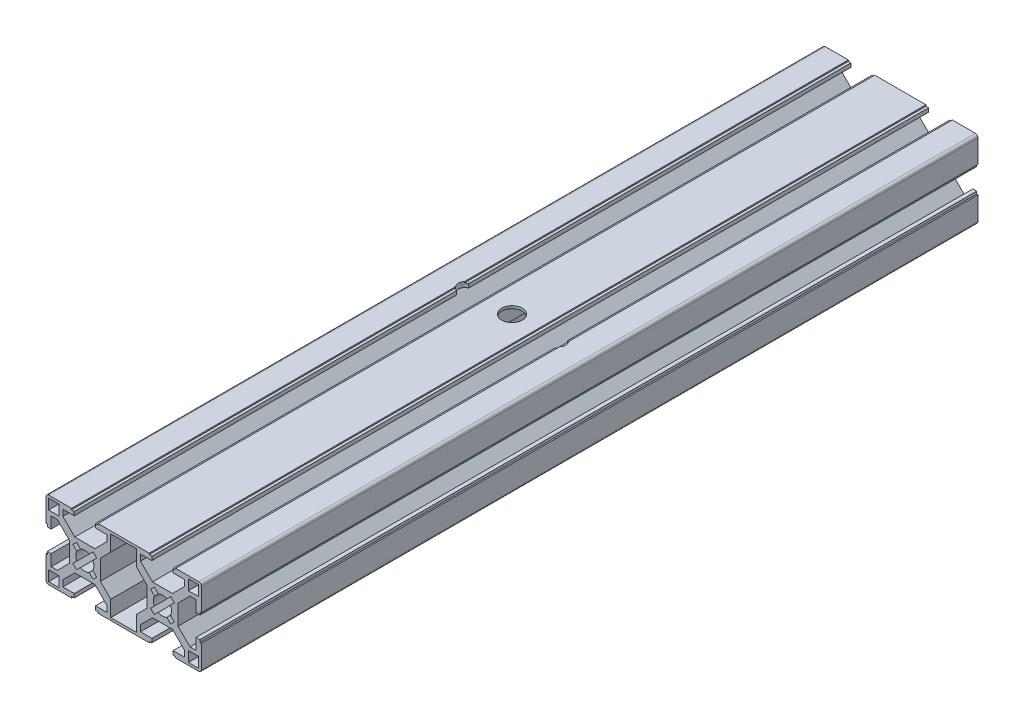
SolidWorks part; units mm, degrees
material "6063-O"
ref_plane "Plano frontal" through (0, 0, 0) normal (0, 0, 1) x (1, 0, 0)
ref_plane "Plano superior" through (0, 0, 0) normal (0, 1, 0) x (1, 0, 0)
ref_plane "Plano direito" through (0, 0, 0) normal (1, 0, 0) x (0, 0, -1)
sketch "Esboço1" plane through (0, 0, 0) normal (0, 0, 1) x (1, 0, 0)
  line L5 (0, 0) -> (-17.7944, 17.7944) construction
  line L6 (0, 3.5) -> (0, 6)
  line L8 (0, 6) -> (-3.8787, 6)
  line L9 (-3.5, 0) -> (-6, 0)
  line L48 (-6, 0) -> (-6, 3.8787)
  line L49 (-3.8787, 6) -> (-8.5, 10.6213)
  line L50 (-6, 3.8787) -> (-10.6213, 8.5)
  line L51 (0, 0) -> (-12.921, 0) construction
  line L52 (-8.5, 13) -> (-4.1, 13)
  line L53 (-4.1, 13) -> (-4.1, 14.5)
  line L54 (-4.1, 14.5) -> (-5.1, 14.5)
  line L55 (-5.1, 14.5) -> (-5.1, 15)
  line L56 (-5.1, 15) -> (-15, 15)
  line L57 (-15, 5.1) -> (-15, 15)
  line L58 (-14.5, 5.1) -> (-15, 5.1)
  line L59 (-14.5, 4.1) -> (-14.5, 5.1)
  line L60 (-13, 4.1) -> (-14.5, 4.1)
  line L61 (-13, 8.5) -> (-13, 4.1)
  line L62 (-1.6646, 3.0788) -> (-3.182, 4.5962)
  line L63 (-3.0788, 1.6646) -> (-4.5962, 3.182)
  line L64 (-4.5962, 3.182) -> (-3.182, 4.5962)
  line L65 (-8.5, 13) -> (-8.5, 10.6213)
  line L66 (-10, 14) -> (-14, 14)
  line L67 (-10, 14) -> (-10, 10)
  line L68 (-10, 10) -> (-14, 10)
  line L69 (-14, 14) -> (-14, 10)
  line L70 (-10, 14) -> (-14, 10) construction
  line L71 (-10, 10) -> (-14, 14) construction
  line L72 (-13, 8.5) -> (-10.6213, 8.5)
  circle A1 centre (0, 0) radius 3.5
  point P25 (-12, 12)
  dimension "D5" = 10.9
  dimension "D9" = 5.5
  dimension "D10" = 2
  dimension "D11" = 4
  dimension "D12" = 4
  dimension "D13" = 1
  dimension "D1" = 7
  dimension "D2" = 6
  dimension "D3" = 3
  dimension "D4" = 9.9
  dimension "D6" = 0.5
  dimension "D7" = 1.5
  dimension "D8" = 15
  dimension "D14" = 6.5
extrude "Ressalto-extrusão1" add sketch "Esboço1" along normal blind 300 contours A1 L6 L8 L49 L65 L52 L53 L54 L55 L56 L57 L58 L59 L60 L61 L72 L50 L48 L9 L63 L64 L62 L69 L66 L67 L68
sketch "Esboço3" plane through (0, 0, 0) normal (1, 0, 0) x (0, 0, -1)
  line L0 (0, 0) -> (-1000, 0) construction
  dimension "D1" = 1000
pattern_circular "PadrãoCircular1" count 4 over 360 about axis through (0, 0, 0) along (0, 0, 1) of "Ressalto-extrusão1"
pattern_linear "Padrão linear1" count 2 spacing 30 along (1, 0, 0) of "Ressalto-extrusão1", "PadrãoCircular1"
sketch "Esboço4" plane through (0, 0, 0) normal (0, 0, -1) x (-1, 0, 0)
  line L0 (-20, 14) -> (-20, -14)
  line L1 (-20, -14) -> (-10, -14)
  line L2 (-10, -14) -> (-10, 14)
  line L3 (-10, 14) -> (-20, 14)
extrude "Corte-extrusão1" cut sketch "Esboço4" against normal through all
fillet "Filete1" radius 1 4 edges at (45, -15, 150) (45, 15, 150) (-15, 15, 150) (-15, -15, 150)
sketch "Sketch1" plane through (0, 15, 0) normal (0, 1, 0) x (1, 0, 0)
  line L0 (-14, 0) -> (44, -300)
  line L1 (15, -150) -> (33.25, -150) construction
  line L2 (15, -150) -> (15, -209.6117) construction
  circle A0 centre (15, -150) radius 4
  circle A1 centre (33.25, -150) radius 2.5
  circle A2 centre (-3.25, -150) radius 2.5
  dimension "D1" = 8
  dimension "D2" = 5
  dimension "D3" = 36.5
extrude "Cut-Extrude1" cut sketch "Sketch1" against normal blind 3 contours L0 A0 | L0 A0 | A1 | A2
ref_plane "Plane1" through (0, 0, 150) normal (0, 0, -1) x (-1, 0, 0)
sketch "Sketch2" plane through (0, 15, 0) normal (0, 1, 0) x (1, 0, 0)
  circle A0 centre (15, -150) radius 4
  dimension "D1" = 8
extrude "Cut-Extrude2" cut sketch "Sketch2" against normal through all
